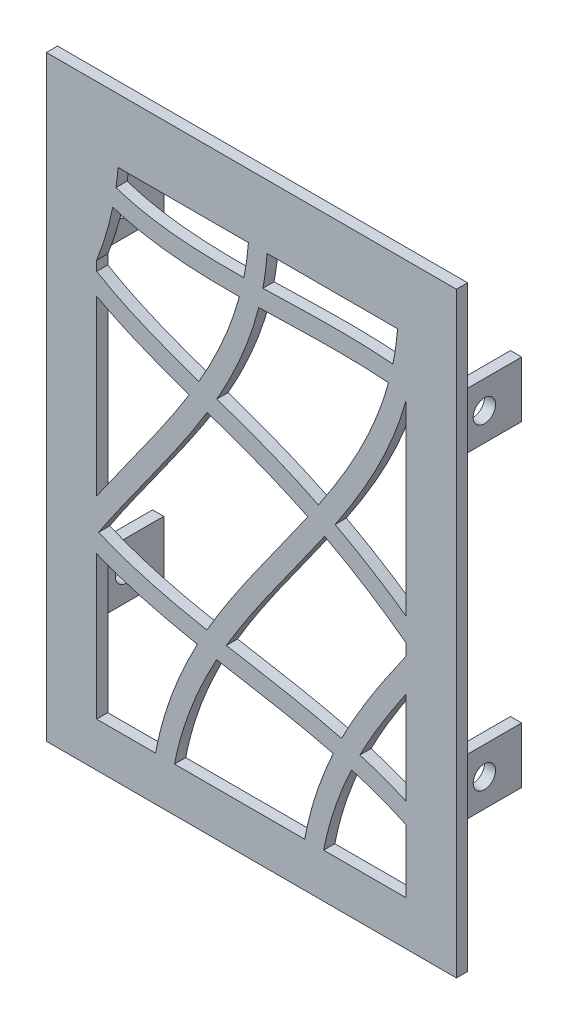
SolidWorks part; units mm, degrees
ref_plane "Front Plane" through (0, 0, 0) normal (0, 0, 1) x (1, 0, 0)
ref_plane "Top Plane" through (0, 0, 0) normal (0, 1, 0) x (1, 0, 0)
ref_plane "Right Plane" through (0, 0, 0) normal (1, 0, 0) x (0, 0, -1)
sketch "Sketch1" plane through (0, 0, 0) normal (0, 0, 1) x (1, 0, 0)
  line L1 (0, 0) -> (110, 0)
  line L2 (0, 0) -> (0, 160)
  line L3 (0, 160) -> (110, 160)
  line L4 (110, 0) -> (110, 160)
  dimension "D1" = 160
  dimension "D2" = 110
extrude "Boss-Extrude1" add sketch "Sketch1" along normal blind 3
sketch "Sketch2" plane through (0, 0, 0) normal (0, 0, -1) x (-1, 0, 0)
  line L0 (0, 160) -> (0, 0) construction
  line L1 (-8.5, 130) -> (-5.5, 130)
  line L2 (-8.5, 130) -> (-8.5, 115)
  line L3 (-8.5, 115) -> (-5.5, 115)
  line L4 (-5.5, 130) -> (-5.5, 115)
  line L5 (-8.5, 45) -> (-5.5, 45)
  line L6 (-8.5, 45) -> (-8.5, 30)
  line L7 (-8.5, 30) -> (-5.5, 30)
  line L8 (-5.5, 45) -> (-5.5, 30)
  line L9 (-110, 160) -> (0, 160) construction
  line L10 (0, 0) -> (-110, 0) construction
  line L11 (-55, 224.1792) -> (-55, -65.648) construction
  line L13 (-101.5, 45) -> (-101.5, 30)
  line L14 (-101.5, 30) -> (-104.5, 30)
  line L15 (-104.5, 45) -> (-104.5, 30)
  line L16 (-101.5, 45) -> (-104.5, 45)
  line L17 (-101.5, 115) -> (-104.5, 115)
  line L18 (-104.5, 130) -> (-104.5, 115)
  line L19 (-101.5, 130) -> (-101.5, 115)
  line L20 (-101.5, 130) -> (-104.5, 130)
  dimension "D1" = 5.5
  dimension "D2" = 3
  dimension "D3" = 15
  dimension "D4" = 30
  dimension "D5" = 3
  dimension "D6" = 5.5
  dimension "D7" = 15
  dimension "D8" = 30
  dimension "D9" = 55
extrude "Boss-Extrude2" add sketch "Sketch2" along normal blind 20
fillet "Fillet1" radius 5 4 edges at (8.5, 37.5, 0) (8.5, 122.5, 0) (101.5, 37.5, 0) (101.5, 122.5, 0)
sketch "Sketch3" plane through (104.5, 0, 0) normal (1, 0, 0) x (0, 0, -1)
  line L0 (20, 30) -> (0, 30) construction
  line L1 (20, 45) -> (20, 30) construction
  line L2 (20, 130) -> (20, 115) construction
  line L3 (20, 130) -> (0, 130) construction
  line L4 (0, 0) -> (0, 160) construction
  circle A0 centre (10, 122.5) radius 3
  circle A1 centre (10, 37.5) radius 3
  dimension "D1" = 6
  dimension "D5" = 6
  dimension "D2" = 7.5
  dimension "D3" = 10
  dimension "D4" = 10
  dimension "D6" = 7.5
extrude "Cut-Extrude1" cut sketch "Sketch3" against normal blind 120
sketch "Sketch5" plane through (0, 0, 0) normal (0, 0, -1) x (-1, 0, 0)
  line L0 (-13.5, 30) -> (-13.5, 45) construction
  line L1 (-96.5, 142.9201) -> (-13.5, 142.9201)
  line L2 (-96.5, 142.9201) -> (-96.5, 11.8857)
  line L3 (-96.5, 11.8857) -> (-13.5, 11.8857)
  line L4 (-13.5, 142.9201) -> (-13.5, 11.8857)
  line L5 (-96.5, 45) -> (-96.5, 30) construction
  spline S0 degree 3 poles (14.4863, 156.7355) (9.5366, 111.5186) (-63.4203, 103.5126) (-115.732, 62.0746) (-134.6244, 34.9262) knots 0 0 0 0 0.515252 1 1 1 1
  spline S1 degree 3 poles (26.9355, 173.3248) (3.6546, 97.9325) (92.9645, 64.2455) (89.492, -7.5452) knots 0 0 0 0 1 1 1 1
  spline S2 degree 3 poles (-146.3978, 100.0496) (-104.0921, 171.4927) (-6.0593, 86.8333) (16.9715, 178.9573) knots 0 0 0 0 1 1 1 1
  spline S3 degree 3 poles (-124.7793, 9.2516) (-84.8261, 61.6782) (-8.1053, 23.0428) (23.3079, 88.5197) knots 0 0 0 0 1 1 1 1
  spline S4 degree 1 poles (-144.2467, 98.7757) (19.3968, 178.351) knots 0 0 1 1 construction
  spline S5 degree 3 poles (-144.2467, 98.7757) (-143.9297, 99.311) (-143.278, 100.382) (-141.9627, 102.4279) (-140.2702, 104.8539) (-138.1734, 107.549) (-135.2906, 110.8716) (-131.5314, 114.5369) (-126.7875, 118.2267) (-121.8232, 121.2758) (-114.9257, 124.5719) (-105.812, 127.3983) (-94.2293, 129.1629) (-82.1864, 129.7428) (-69.8838, 129.5994) (-57.519, 129.2087) (-45.2806, 129.058) (-33.3468, 129.6473) (-21.8913, 131.4962) (-11.1056, 135.1525) (-2.8945, 140.1675) (3.0422, 145.594) (7.1406, 150.4169) (10.8542, 156.0383) (13.6086, 161.4267) (15.5989, 166.1861) (16.9826, 169.9855) (18.0442, 173.3539) (18.8349, 176.1628) (19.2152, 177.6246) (19.3968, 178.351) knots 0 0 0 0 0.007812 0.015625 0.03125 0.046875 0.0625 0.09375 0.125 0.15625 0.1875 0.25 0.3125 0.375 0.4375 0.5 0.5625 0.625 0.6875 0.75 0.8125 0.84375 0.875 0.90625 0.9375 0.953125 0.96875 0.984375 0.992188 1 1 1 1
  spline S6 degree 3 poles (-13.0645, 173.3248) (-36.3454, 97.9325) (52.9645, 64.2455) (49.492, -7.5452) knots 0 0 0 0 1 1 1 1
  spline S7 degree 3 poles (-53.0645, 173.3248) (-76.3454, 97.9325) (12.9645, 64.2455) (9.492, -7.5452) knots 0 0 0 0 1 1 1 1
  spline S8 degree 3 poles (-93.0645, 173.3248) (-116.3454, 97.9325) (-27.0355, 64.2455) (-30.508, -7.5452) knots 0 0 0 0 1 1 1 1
  spline S9 degree 3 poles (-133.0645, 173.3248) (-156.3454, 97.9325) (-67.0355, 64.2455) (-70.508, -7.5452) knots 0 0 0 0 1 1 1 1
  spline S10 degree 3 poles (-173.0645, 173.3248) (-196.3454, 97.9325) (-107.0355, 64.2455) (-110.508, -7.5452) knots 0 0 0 0 1 1 1 1
  spline S11 degree 1 poles (-135.4532, 174.0625) (-73.0051, -7.4244) knots 0 0 1 1 construction
  spline S12 degree 3 poles (-135.4532, 174.0625) (-135.8213, 172.8707) (-136.5188, 170.4501) (-137.6781, 165.7422) (-138.7361, 159.9734) (-139.4025, 153.2672) (-139.5396, 144.5875) (-138.3939, 134.2145) (-135.2332, 122.4526) (-130.6196, 111.2794) (-122.9674, 97.0098) (-111.3845, 80.0326) (-99.154, 63.3669) (-90.1777, 49.758) (-84.1439, 39.3044) (-79.0969, 28.4948) (-75.9467, 19.0962) (-74.1967, 11.2788) (-73.3036, 5.2501) (-72.9383, 0.0671) (-72.8908, -4.172) (-72.9529, -6.3456) (-73.0051, -7.4244) knots 0 0 0 0 0.015625 0.03125 0.0625 0.09375 0.125 0.1875 0.25 0.3125 0.375 0.5 0.625 0.6875 0.75 0.8125 0.875 0.90625 0.9375 0.96875 0.984375 1 1 1 1
  spline S13 degree 1 poles (-95.4532, 174.0625) (-33.0051, -7.4244) knots 0 0 1 1 construction
  spline S14 degree 3 poles (-95.4532, 174.0625) (-95.8213, 172.8707) (-96.5188, 170.4501) (-97.6781, 165.7422) (-98.7361, 159.9734) (-99.4025, 153.2672) (-99.5396, 144.5875) (-98.3939, 134.2145) (-95.2332, 122.4526) (-90.6196, 111.2794) (-82.9674, 97.0098) (-71.3845, 80.0326) (-59.154, 63.3669) (-50.1777, 49.758) (-44.1439, 39.3044) (-39.0969, 28.4948) (-35.9467, 19.0962) (-34.1967, 11.2788) (-33.3036, 5.2501) (-32.9383, 0.0671) (-32.8908, -4.172) (-32.9529, -6.3456) (-33.0051, -7.4244) knots 0 0 0 0 0.015625 0.03125 0.0625 0.09375 0.125 0.1875 0.25 0.3125 0.375 0.5 0.625 0.6875 0.75 0.8125 0.875 0.90625 0.9375 0.96875 0.984375 1 1 1 1
  spline S15 degree 1 poles (-55.4532, 174.0625) (6.9949, -7.4244) knots 0 0 1 1 construction
  spline S16 degree 3 poles (-55.4532, 174.0625) (-55.8213, 172.8707) (-56.5188, 170.4501) (-57.6781, 165.7422) (-58.7361, 159.9734) (-59.4025, 153.2672) (-59.5396, 144.5875) (-58.3939, 134.2145) (-55.2332, 122.4526) (-50.6196, 111.2794) (-42.9674, 97.0098) (-31.3845, 80.0326) (-19.154, 63.3669) (-10.1777, 49.758) (-4.1439, 39.3044) (0.9031, 28.4948) (4.0533, 19.0962) (5.8033, 11.2788) (6.6964, 5.2501) (7.0617, 0.0671) (7.1092, -4.172) (7.0471, -6.3456) (6.9949, -7.4244) knots 0 0 0 0 0.015625 0.03125 0.0625 0.09375 0.125 0.1875 0.25 0.3125 0.375 0.5 0.625 0.6875 0.75 0.8125 0.875 0.90625 0.9375 0.96875 0.984375 1 1 1 1
  spline S17 degree 1 poles (-15.4532, 174.0625) (46.9949, -7.4244) knots 0 0 1 1 construction
  spline S18 degree 3 poles (-15.4532, 174.0625) (-15.8213, 172.8707) (-16.5188, 170.4501) (-17.6781, 165.7422) (-18.7361, 159.9734) (-19.4025, 153.2672) (-19.5396, 144.5875) (-18.3939, 134.2145) (-15.2332, 122.4526) (-10.6196, 111.2794) (-2.9674, 97.0098) (8.6155, 80.0326) (20.846, 63.3669) (29.8223, 49.758) (35.8561, 39.3044) (40.9031, 28.4948) (44.0533, 19.0962) (45.8033, 11.2788) (46.6964, 5.2501) (47.0617, 0.0671) (47.1092, -4.172) (47.0471, -6.3456) (46.9949, -7.4244) knots 0 0 0 0 0.015625 0.03125 0.0625 0.09375 0.125 0.1875 0.25 0.3125 0.375 0.5 0.625 0.6875 0.75 0.8125 0.875 0.90625 0.9375 0.96875 0.984375 1 1 1 1
  spline S19 degree 1 poles (12.0012, 157.0075) (-136.6764, 36.3542) knots 0 0 1 1 construction
  spline S20 degree 3 poles (12.0012, 157.0075) (11.9293, 156.3511) (11.7678, 155.0274) (11.3919, 152.4883) (10.8172, 149.444) (9.9697, 146.0109) (8.638, 141.706) (6.613, 136.8138) (3.6565, 131.6396) (0.2146, 127.0767) (-4.9748, 121.7022) (-12.5063, 116.1337) (-22.9008, 110.7958) (-34.2653, 106.3293) (-46.1816, 102.229) (-58.253, 97.9811) (-70.0122, 92.9894) (-84.9727, 85.2615) (-98.8972, 75.9812) (-111.6764, 65.185) (-120.668, 56.344) (-127.6506, 48.3624) (-132.9136, 41.6234) (-135.4459, 38.1224) (-136.6764, 36.3542) knots 0 0 0 0 0.007812 0.015625 0.03125 0.046875 0.0625 0.09375 0.125 0.15625 0.1875 0.25 0.3125 0.375 0.4375 0.5 0.5625 0.625 0.75 0.8125 0.875 0.9375 0.96875 1 1 1 1
  spline S21 degree 1 poles (-130.6758, 172.5872) (-68.0109, -7.6659) knots 0 0 1 1 construction
  spline S22 degree 3 poles (-130.6758, 172.5872) (-131.025, 171.4564) (-131.6875, 169.1572) (-132.7838, 164.7043) (-133.7804, 159.268) (-134.4052, 152.976) (-134.533, 144.8534) (-133.4628, 135.1551) (-130.492, 124.0841) (-126.1032, 113.4443) (-118.7263, 99.6776) (-107.3538, 82.9896) (-95.0814, 66.2714) (-85.9336, 52.4068) (-79.7151, 41.6383) (-74.4522, 30.3747) (-71.131, 20.4756) (-69.2768, 12.1947) (-68.3283, 5.7934) (-67.9401, 0.286) (-67.8897, -4.2161) (-67.9555, -6.5214) (-68.0109, -7.6659) knots 0 0 0 0 0.015625 0.03125 0.0625 0.09375 0.125 0.1875 0.25 0.3125 0.375 0.5 0.625 0.6875 0.75 0.8125 0.875 0.90625 0.9375 0.96875 0.984375 1 1 1 1
  spline S23 degree 1 poles (-90.6758, 172.5872) (-28.0109, -7.6659) knots 0 0 1 1 construction
  spline S24 degree 3 poles (-90.6758, 172.5872) (-91.025, 171.4564) (-91.6875, 169.1572) (-92.7838, 164.7043) (-93.7804, 159.268) (-94.4052, 152.976) (-94.533, 144.8534) (-93.4628, 135.1551) (-90.492, 124.0841) (-86.1032, 113.4443) (-78.7263, 99.6776) (-67.3538, 82.9896) (-55.0814, 66.2714) (-45.9336, 52.4068) (-39.7151, 41.6383) (-34.4522, 30.3747) (-31.131, 20.4756) (-29.2768, 12.1947) (-28.3283, 5.7934) (-27.9401, 0.286) (-27.8897, -4.2161) (-27.9555, -6.5214) (-28.0109, -7.6659) knots 0 0 0 0 0.015625 0.03125 0.0625 0.09375 0.125 0.1875 0.25 0.3125 0.375 0.5 0.625 0.6875 0.75 0.8125 0.875 0.90625 0.9375 0.96875 0.984375 1 1 1 1
  spline S25 degree 1 poles (-50.6758, 172.5872) (11.9891, -7.6659) knots 0 0 1 1 construction
  spline S26 degree 3 poles (-50.6758, 172.5872) (-51.025, 171.4564) (-51.6875, 169.1572) (-52.7838, 164.7043) (-53.7804, 159.268) (-54.4052, 152.976) (-54.533, 144.8534) (-53.4628, 135.1551) (-50.492, 124.0841) (-46.1032, 113.4443) (-38.7263, 99.6776) (-27.3538, 82.9896) (-15.0814, 66.2714) (-5.9336, 52.4068) (0.2849, 41.6383) (5.5478, 30.3747) (8.869, 20.4756) (10.7232, 12.1947) (11.6717, 5.7934) (12.0599, 0.286) (12.1103, -4.2161) (12.0445, -6.5214) (11.9891, -7.6659) knots 0 0 0 0 0.015625 0.03125 0.0625 0.09375 0.125 0.1875 0.25 0.3125 0.375 0.5 0.625 0.6875 0.75 0.8125 0.875 0.90625 0.9375 0.96875 0.984375 1 1 1 1
  spline S27 degree 1 poles (-10.6758, 172.5872) (51.9891, -7.6659) knots 0 0 1 1 construction
  spline S28 degree 3 poles (-10.6758, 172.5872) (-11.025, 171.4564) (-11.6875, 169.1572) (-12.7838, 164.7043) (-13.7804, 159.268) (-14.4052, 152.976) (-14.533, 144.8534) (-13.4628, 135.1551) (-10.492, 124.0841) (-6.1032, 113.4443) (1.2737, 99.6776) (12.6462, 82.9896) (24.9186, 66.2714) (34.0664, 52.4068) (40.2849, 41.6383) (45.5478, 30.3747) (48.869, 20.4756) (50.7232, 12.1947) (51.6717, 5.7934) (52.0599, 0.286) (52.1103, -4.2161) (52.0445, -6.5214) (51.9891, -7.6659) knots 0 0 0 0 0.015625 0.03125 0.0625 0.09375 0.125 0.1875 0.25 0.3125 0.375 0.5 0.625 0.6875 0.75 0.8125 0.875 0.90625 0.9375 0.96875 0.984375 1 1 1 1
  spline S29 degree 1 poles (16.9715, 156.4634) (-132.5723, 33.4982) knots 0 0 1 1 construction
  spline S30 degree 3 poles (16.9715, 156.4634) (16.8951, 155.7655) (16.7237, 154.3601) (16.3225, 151.6504) (15.7065, 148.3857) (14.7913, 144.6769) (13.3433, 139.994) (11.1207, 134.6189) (7.8454, 128.8844) (4.0229, 123.8174) (-1.7141, 117.8788) (-9.9119, 111.8338) (-20.8899, 106.2104) (-36.4751, 100.0887) (-52.6864, 94.911) (-67.8766, 88.4631) (-82.41, 80.9564) (-95.91, 71.9575) (-108.3042, 61.4869) (-117.0266, 52.9106) (-123.8043, 45.1635) (-128.9157, 38.6189) (-131.3767, 35.2163) (-132.5723, 33.4982) knots 0 0 0 0 0.007812 0.015625 0.03125 0.046875 0.0625 0.09375 0.125 0.15625 0.1875 0.25 0.3125 0.375 0.5 0.5625 0.625 0.75 0.8125 0.875 0.9375 0.96875 1 1 1 1
  spline S31 degree 1 poles (-122.7909, 7.7362) (25.5619, 87.4383) knots 0 0 1 1 construction
  spline S32 degree 3 poles (-122.7909, 7.7362) (-122.1941, 8.5193) (-120.9588, 10.0745) (-118.4502, 12.9808) (-115.1886, 16.3208) (-111.1024, 19.8756) (-105.4313, 24.0712) (-97.9515, 28.3843) (-88.4323, 32.351) (-78.4699, 35.3754) (-64.7467, 38.5094) (-50.6039, 40.8395) (-36.5221, 43.4984) (-26.109, 45.9515) (-15.9642, 49.1632) (-6.2152, 53.44) (2.9938, 59.0882) (10.0814, 65.1798) (15.3168, 71.0162) (19.0058, 75.9028) (21.8718, 80.4336) (24.0225, 84.3291) (25.0652, 86.403) (25.5619, 87.4383) knots 0 0 0 0 0.015625 0.03125 0.0625 0.09375 0.125 0.1875 0.25 0.3125 0.375 0.5 0.5625 0.625 0.6875 0.75 0.8125 0.875 0.90625 0.9375 0.96875 0.984375 1 1 1 1
  spline S33 degree 1 poles (-148.549, 101.3234) (14.5461, 179.5637) knots 0 0 1 1 construction
  spline S34 degree 3 poles (-148.549, 101.3234) (-148.2114, 101.8934) (-147.518, 103.0329) (-146.1132, 105.2182) (-144.2992, 107.8186) (-142.0404, 110.7224) (-138.9208, 114.3183) (-134.8289, 118.3095) (-129.6421, 122.3442) (-124.214, 125.6777) (-116.7035, 129.2654) (-106.8927, 132.2992) (-94.6858, 134.1504) (-82.2418, 134.7452) (-69.7434, 134.5976) (-57.3758, 134.2067) (-45.3337, 134.0605) (-33.8217, 134.6344) (-23.0491, 136.3838) (-13.2075, 139.7363) (-5.8823, 144.2166) (-0.5733, 149.067) (3.123, 153.4138) (6.5168, 158.5463) (9.0723, 163.5408) (10.9385, 168.0025) (12.2449, 171.5886) (13.2537, 174.7889) (14.0081, 177.4685) (14.3724, 178.8686) (14.5461, 179.5637) knots 0 0 0 0 0.007812 0.015625 0.03125 0.046875 0.0625 0.09375 0.125 0.15625 0.1875 0.25 0.3125 0.375 0.4375 0.5 0.5625 0.625 0.6875 0.75 0.8125 0.84375 0.875 0.90625 0.9375 0.953125 0.96875 0.984375 0.992188 1 1 1 1
  spline S35 degree 1 poles (-126.7677, 10.7669) (21.0539, 89.601) knots 0 0 1 1 construction
  spline S36 degree 3 poles (-126.7677, 10.7669) (-126.1303, 11.6033) (-124.8117, 13.2633) (-122.126, 16.3751) (-118.6263, 19.9591) (-114.2359, 23.7787) (-108.1479, 28.2824) (-100.1532, 32.8889) (-90.1003, 37.0733) (-79.7292, 40.2184) (-65.646, 43.4311) (-51.421, 45.7723) (-37.5352, 48.3964) (-27.4132, 50.7832) (-17.704, 53.8609) (-8.5206, 57.8946) (0.041, 63.1504) (6.5932, 68.782) (11.4489, 74.1942) (14.8854, 78.7451) (17.5717, 82.9908) (19.5972, 86.659) (20.5843, 88.6222) (21.0539, 89.601) knots 0 0 0 0 0.015625 0.03125 0.0625 0.09375 0.125 0.1875 0.25 0.3125 0.375 0.5 0.5625 0.625 0.6875 0.75 0.8125 0.875 0.90625 0.9375 0.96875 0.984375 1 1 1 1
  dimension "D5" = 0
  dimension "D6" = 0
  dimension "D1" = 2.5
  dimension "D2" = 2.5
  dimension "D3" = 2.5
  dimension "D4" = 2.5
extrude "Cut-Extrude2" cut sketch "Sketch5" against normal blind 120 contours L2 S36 S12 | S32 L2 L3 S12 | S32 S22 L3 S14 | S32 S24 L3 L4 | S24 S36 L4 S16 S30 | S22 S36 S14 S30 L2 | S20 S14 L2 | S5 S24 S20 S16 | S24 S34 S16 L1 | S26 S34 S18 L1 | S5 S26 S20 L4 S18 | L4 S30 S26
